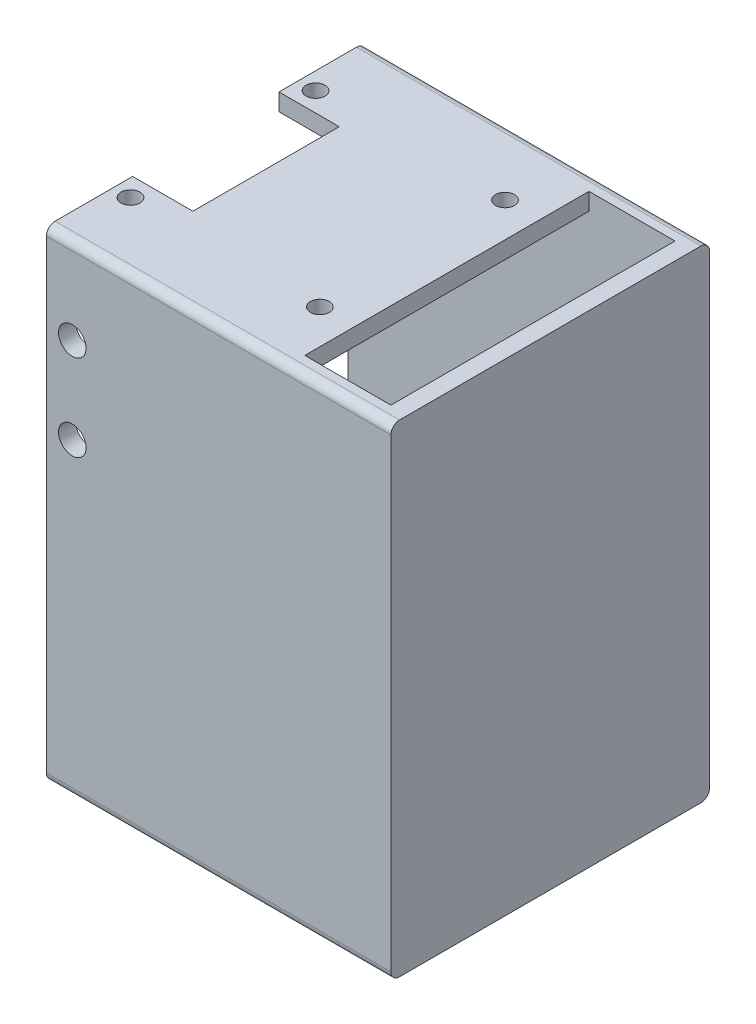
SolidWorks part; units mm, degrees
ref_plane "前视基准面" through (0, 0, 0) normal (0, 0, 1) x (1, 0, 0)
ref_plane "上视基准面" through (0, 0, 0) normal (0, 1, 0) x (1, 0, 0)
ref_plane "右视基准面" through (0, 0, 0) normal (1, 0, 0) x (0, 0, -1)
other "Configuration Table"
sketch "草图1" plane through (0, 0, 0) normal (0, 1, 0) x (1, 0, 0)
  line L1 (-20, -18.5) -> (20, -18.5)
  line L2 (-20, -18.5) -> (-20, 18.5)
  line L3 (-20, 18.5) -> (20, 18.5)
  line L4 (20, -18.5) -> (20, 18.5)
  line L5 (-20, -18.5) -> (20, 18.5) construction
  line L6 (-20, 18.5) -> (20, -18.5) construction
  point P0 (0, 0)
  dimension "D1" = 40
  dimension "D2" = 37
extrude "凸台-拉伸1" add sketch "草图1" along normal blind 51
sketch "草图3" plane through (-20, 0, 0) normal (-1, 0, 0) x (0, 0, 1)
  line L8 (-16.5, 2) -> (16.5, 2)
  line L9 (16.5, 2) -> (16.5, 49)
  line L10 (16.5, 49) -> (-16.5, 49)
  line L11 (-16.5, 49) -> (-16.5, 2)
  line L12 (-16.5, 2) -> (16.5, 2)
  line L13 (16.5, 2) -> (16.5, 49)
  line L14 (16.5, 49) -> (-16.5, 49)
  line L15 (-16.5, 49) -> (-16.5, 2)
  dimension "D1" = 2
extrude "切除-拉伸2" cut sketch "草图3" against normal blind 38
sketch "草图4" plane through (0, 51, 0) normal (0, 1, 0) x (1, 0, 0)
  line L1 (8, 16.5) -> (18, 16.5)
  line L2 (8, 16.5) -> (8, -16.5)
  line L3 (8, -16.5) -> (18, -16.5)
  line L4 (18, 16.5) -> (18, -16.5)
  line L5 (8, 16.5) -> (18, -16.5) construction
  line L6 (8, -16.5) -> (18, 16.5) construction
  line L7 (20, 18.5) -> (-20, 18.5) construction
  line L8 (-20, -18.5) -> (20, -18.5) construction
  line L10 (20, -18.5) -> (20, 18.5) construction
  point P0 (13, 0)
  dimension "D1" = 2
  dimension "D2" = 2
  dimension "D3" = 2
  dimension "D4" = 10
extrude "切除-拉伸3" cut sketch "草图4" against normal up to next
sketch "草图5" plane through (0, 51, 0) normal (0, 1, 0) x (1, 0, 0)
  line L0 (-20, 18.5) -> (-20, -18.5) construction
  line L1 (-13, -8.5) -> (-20, -8.5)
  line L2 (-13, -8.5) -> (-13, 8.5)
  line L3 (-13, 8.5) -> (-20, 8.5)
  line L4 (-20, -8.5) -> (-20, 8.5)
  line L5 (-13, -8.5) -> (-20, 8.5) construction
  line L6 (-13, 8.5) -> (-20, -8.5) construction
  line L7 (20, 18.5) -> (-20, 18.5) construction
  line L8 (-20, -18.5) -> (20, -18.5) construction
  point P0 (-16.5, 0)
  dimension "D1" = 7
  dimension "D2" = 10
  dimension "10" = 10
  dimension "D4" = 7
  dimension "D5" = 17
extrude "切除-拉伸4" cut sketch "草图5" against normal up to next
sketch "草图6" plane through (0, 51, 0) normal (0, 1, 0) x (1, 0, 0)
  line L1 (-20, 18.5) -> (-20, 8.5) construction
  line L2 (-25.3028, 0) -> (24.8795, 0) construction
  circle A0 centre (-18, 10.75) radius 1.1
  circle A1 centre (-18, -10.75) radius 1.1
  circle A2 centre (4, 10.75) radius 1.1
  circle A3 centre (4, -10.75) radius 1.1
  dimension "D3" = 2.2
  dimension "D4" = 22
  dimension "D1" = 2.2
  dimension "D2" = 2
  dimension "D5" = 21.5
extrude "切除-拉伸5" cut sketch "草图6" against normal up to next
sketch "草图7" plane through (-20, 0, 0) normal (-1, 0, 0) x (0, 0, 1)
  line L0 (-18.5, 51) -> (-18.5, 0) construction
  line L1 (-18.5, 0) -> (18.5, 0)
  line L2 (-18.5, 0) -> (-18.5, -5)
  line L3 (-18.5, -5) -> (18.5, -5)
  line L4 (18.5, 0) -> (18.5, -5)
  line L5 (18.5, 51) -> (18.5, 0) construction
  dimension "D1" = 5
extrude "凸台-拉伸2" add sketch "草图7" against normal up to surface (40 mm away) up to face at (20, 25.5, 0)
sketch "草图9" plane through (-20, 0, 0) normal (-1, 0, 0) x (0, 0, 1)
  line L0 (0, -10.9659) -> (0, 55.8964) construction
  line L1 (-18.5, -5) -> (18.5, -5) construction
  line L2 (-18.5, 51) -> (-18.5, -5) construction
  circle A0 centre (-10, -2) radius 1.6
  circle A2 centre (10, -2) radius 1.6
  circle A3 centre (-15.5, -2) radius 1.1
  circle A4 centre (15.5, -2) radius 1.1
  dimension "D1" = 3.2
  dimension "D2" = 3
  dimension "D3" = 20
  dimension "D4" = 2.2
  dimension "D5" = 3
extrude "切除-拉伸6" cut sketch "草图9" against normal blind 5
sketch "草图12" plane through (0, 0, -18.5) normal (0, 0, -1) x (-1, 0, 0)
  line L0 (17, 49) -> (17, 24.3545) construction
  line L1 (20, 49) -> (14, 49) construction
  line L2 (20, 49) -> (20, 28) construction
  line L3 (20, 28) -> (14, 28) construction
  line L4 (20, 2) -> (20, 49)
  line L5 (-18, 2) -> (20, 2)
  line L6 (-18, 51) -> (-18, 2)
  line L7 (20, 49) -> (-8, 49)
  line L8 (20, 28) -> (20, 49) construction
  line L11 (20, 49) -> (14, 49) construction
  line L12 (14, 49) -> (14, 28) construction
  line L19 (-8, 51) -> (-18, 51)
  line L21 (-8, 49) -> (-8, 51)
  circle A0 centre (17, 41) radius 1.6
  circle A1 centre (17, 31) radius 1.6
  dimension "D4" = 3.2
  dimension "D6" = 3.2
  dimension "D2" = 6
  dimension "D3" = 21
  dimension "D5" = 8
  dimension "D7" = 3
  dimension "D1" = 0
extrude "切除-拉伸7" cut sketch "草图12" against normal up to surface (37 mm away) up to face at (0, 23, 18.5)
fillet "圆角1" radius 1 4 edges at (0, 51, 18.5) (0, 51, -18.5) (0, -5, -18.5) (0, -5, 18.5)
